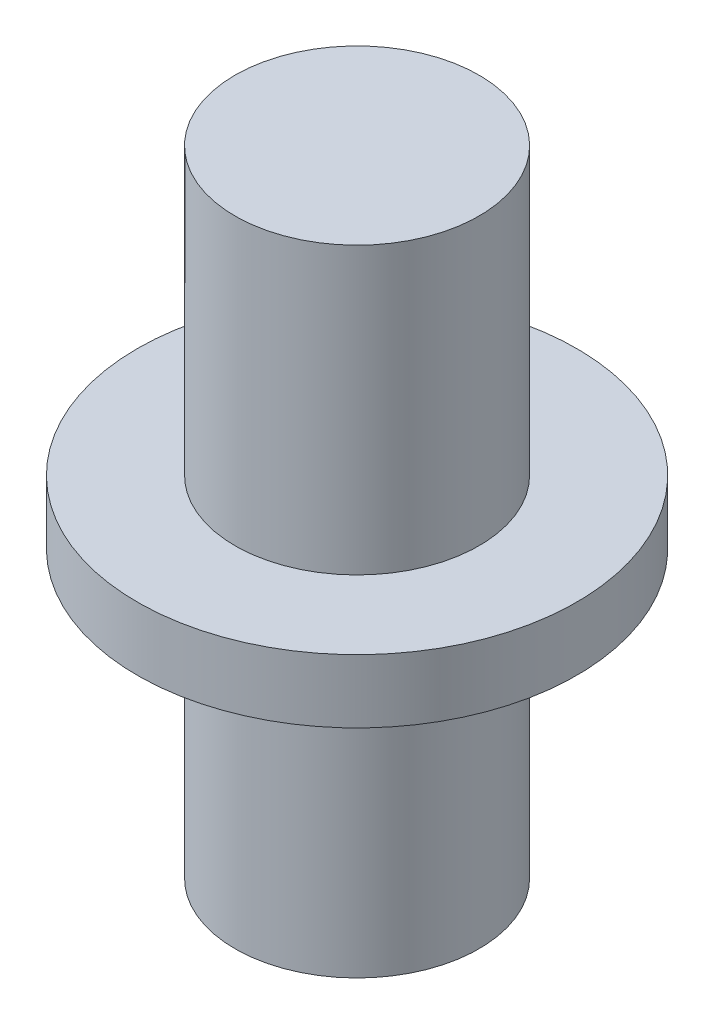
SolidWorks part; units mm, degrees
ref_plane "前视基准面" through (0, 0, 0) normal (0, 0, 1) x (1, 0, 0)
ref_plane "上视基准面" through (0, 0, 0) normal (0, 1, 0) x (1, 0, 0)
ref_plane "右视基准面" through (0, 0, 0) normal (1, 0, 0) x (0, 0, -1)
sketch "草图1" plane through (0, 0, 0) normal (0, 0, 1) x (1, 0, 0)
  line L0 (0, 13) -> (0, 0)
  line L1 (0, 13) -> (2.5, 13)
  line L2 (2.5, 13) -> (2.5, 7.15)
  line L3 (2.5, 7.15) -> (4.5, 7.15)
  line L4 (4.5, 7.15) -> (4.5, 5.85)
  line L5 (4.5, 5.85) -> (2.5, 5.85)
  line L6 (2.5, 5.85) -> (2.5, 0)
  line L7 (2.5, 0) -> (0, 0)
  line L8 (0, 6.5) -> (7.9284, 6.5) construction
  point P11 (2.5, 2.8665)
  point P12 (7.9284, 7.106)
  point P13 (0, -0.2298)
  point P14 (0, 0)
  dimension "D1" = 2.5
  dimension "D2" = 13
  dimension "D3" = 1.3
  dimension "D4" = 4.5
  dimension "D5" = 2.5
  dimension "D6" = 6.5
revolve "旋转1" add sketch "草图1" angle 360 about L0
